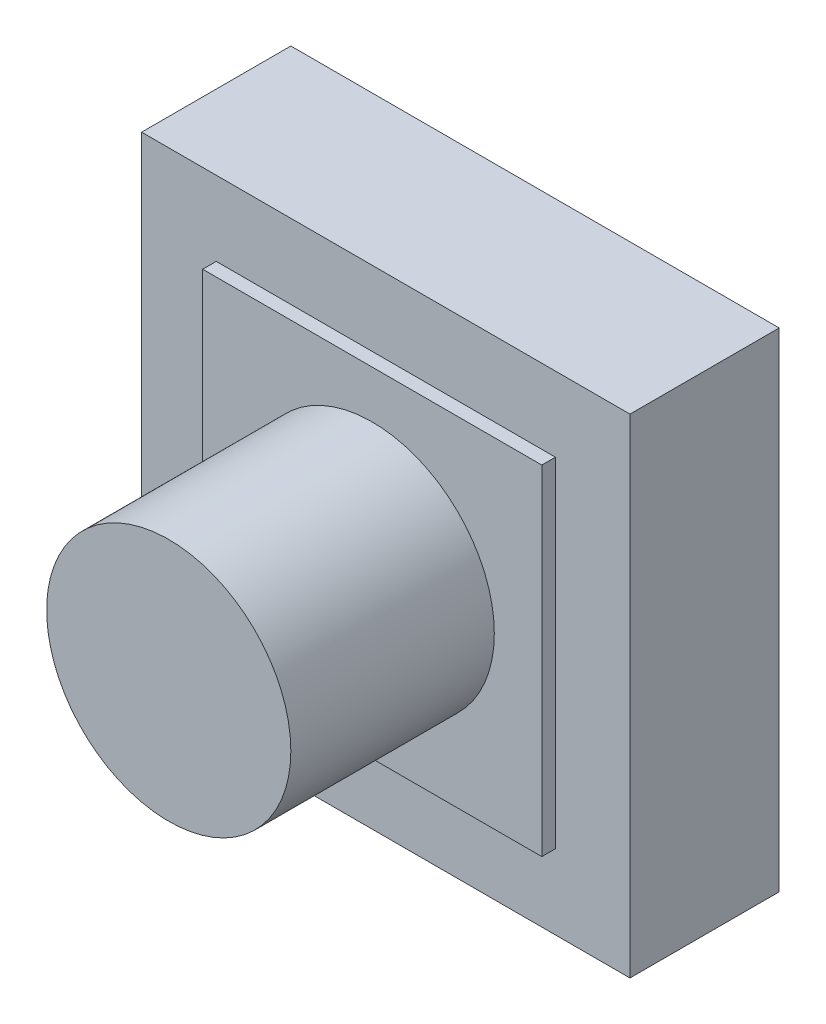
SolidWorks part; units mm, degrees
ref_plane "前视基准面" through (0, 0, 0) normal (0, 0, 1) x (1, 0, 0)
ref_plane "上视基准面" through (0, 0, 0) normal (0, 1, 0) x (1, 0, 0)
ref_plane "右视基准面" through (0, 0, 0) normal (1, 0, 0) x (0, 0, -1)
other "Configuration Table"
sketch "草图1" plane through (0, 0, 0) normal (0, 0, 1) x (1, 0, 0)
  line L1 (-18, -18) -> (18, -18)
  line L2 (-18, -18) -> (-18, 18)
  line L3 (-18, 18) -> (18, 18)
  line L4 (18, -18) -> (18, 18)
  line L5 (-18, -18) -> (18, 18) construction
  line L6 (-18, 18) -> (18, -18) construction
  point P0 (0, 0)
  dimension "D1" = 36
  dimension "D2" = 36
extrude "凸台-拉伸1" add sketch "草图1" along normal blind 11
sketch "草图2" plane through (0, 0, 11) normal (0, 0, 1) x (1, 0, 0)
  line L1 (-12.5, -12.5) -> (12.5, -12.5)
  line L2 (-12.5, -12.5) -> (-12.5, 12.5)
  line L3 (-12.5, 12.5) -> (12.5, 12.5)
  line L4 (12.5, -12.5) -> (12.5, 12.5)
  line L5 (-12.5, -12.5) -> (12.5, 12.5) construction
  line L6 (-12.5, 12.5) -> (12.5, -12.5) construction
  point P0 (0, 0)
  dimension "D1" = 25
  dimension "D2" = 25
extrude "凸台-拉伸2" add sketch "草图2" along normal blind 1
sketch "草图3" plane through (0, 0, 12) normal (0, 0, 1) x (1, 0, 0)
  circle A0 centre (0, 0) radius 9
  dimension "D1" = 18
extrude "凸台-拉伸3" add sketch "草图3" along normal blind 15
